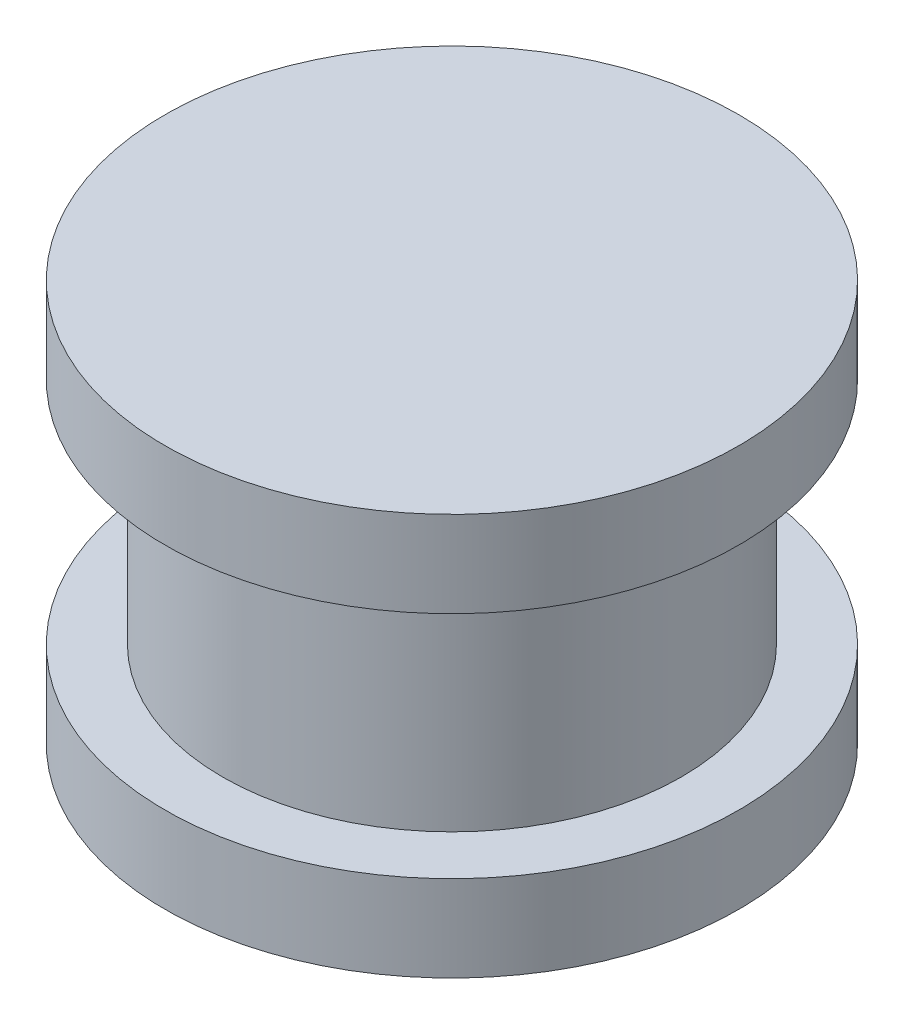
SolidWorks part; units mm, degrees
ref_plane "Plan de face" through (0, 0, 0) normal (0, 0, 1) x (1, 0, 0)
ref_plane "Plan de dessus" through (0, 0, 0) normal (0, 1, 0) x (1, 0, 0)
ref_plane "Plan de droite" through (0, 0, 0) normal (1, 0, 0) x (0, 0, -1)
sketch "Esquisse1" plane through (0, 0, 0) normal (0, 0, 1) x (1, 0, 0)
  line L0 (0, -0.35) -> (0, 0.35)
  line L1 (0, 0.35) -> (0.5, 0.35)
  line L2 (0.5, 0.35) -> (0.5, 0.2)
  line L3 (0.5, 0.2) -> (0.4, 0.2)
  line L4 (0.4, 0.2) -> (0.4, -0.2)
  line L5 (0.4, -0.2) -> (0.5, -0.2)
  line L6 (0.5, -0.2) -> (0.5, -0.35)
  line L7 (0.5, -0.35) -> (0, -0.35)
  line L8 (0, 0) -> (0.4, 0) construction
  point P4 (0, 0)
  dimension "D1" = 0.7
  dimension "D2" = 0.4
  dimension "D3" = 0.5
  dimension "D4" = 0.4
revolve "Révolution1" add sketch "Esquisse1" angle 360 about L0
scale "Echelle1" scale about centroid uniform scaling yes scale factor 0.69
